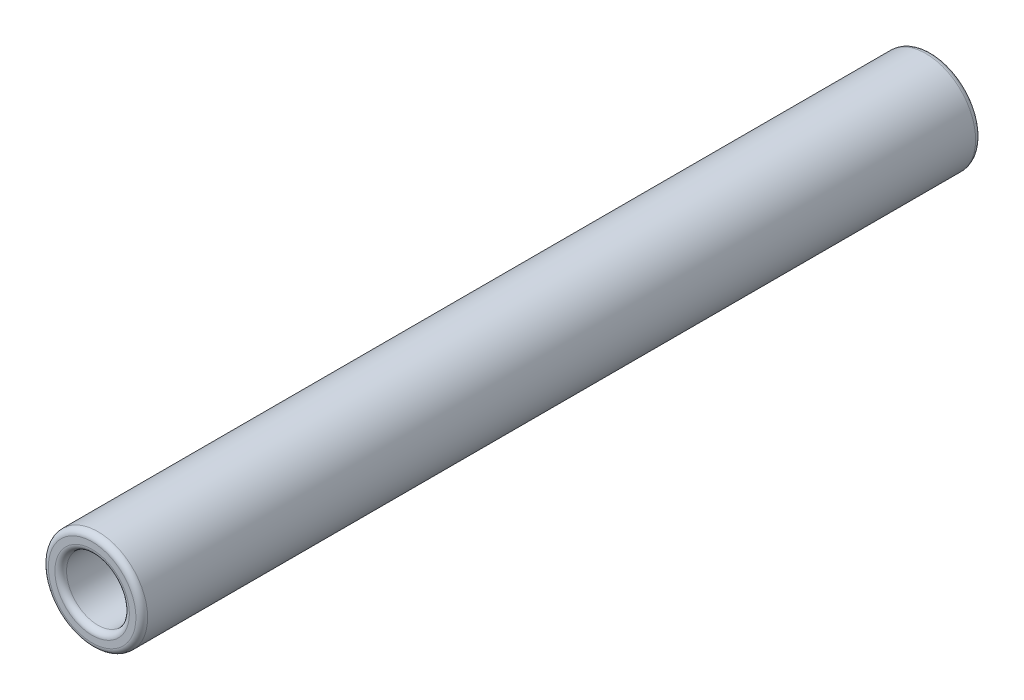
SolidWorks part; units mm, degrees
ref_plane "Front Plane" through (0, 0, 0) normal (0, 0, 1) x (1, 0, 0)
ref_plane "Top Plane" through (0, 0, 0) normal (0, 1, 0) x (1, 0, 0)
ref_plane "Right Plane" through (0, 0, 0) normal (1, 0, 0) x (0, 0, -1)
sketch "Sketch2" plane through (0, 0, 0) normal (0, 0, 1) x (1, 0, 0)
  circle A0 centre (0, 0) radius 8.636
  circle A1 centre (0, 0) radius 5.461
  dimension "D1" = 17.272
  dimension "D2" = 3.175
extrude "Boss-Extrude1" add sketch "Sketch2" along normal blind 146.05 contours A0
fillet "Fillet1" radius 1.016 4 edges at (5.461, 0, 146.05) (8.636, 0, 146.05) (5.461, 0, 0) (8.636, 0, 0)
